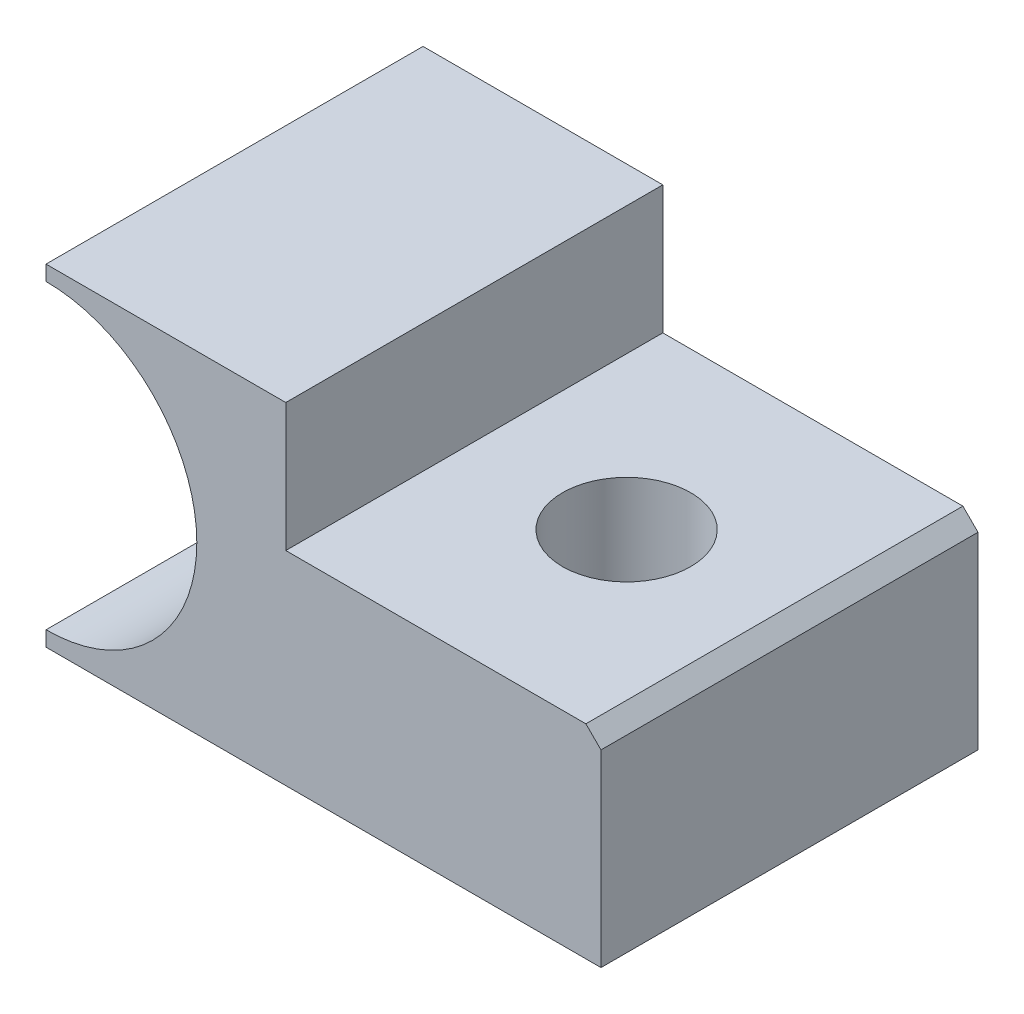
SolidWorks part; units mm, degrees
material "AISI Type A2 Tool Steel Custom"
ref_plane "Front Plane" through (0, 0, 0) normal (0, 0, 1) x (1, 0, 0)
ref_plane "Top Plane" through (0, 0, 0) normal (0, 1, 0) x (1, 0, 0)
ref_plane "Right Plane" through (0, 0, 0) normal (1, 0, 0) x (0, 0, -1)
sketch "Sketch1" plane through (0, 0, 0) normal (0, 0, 1) x (1, 0, 0)
  line L4 (46.736, 0) -> (46.736, 17.145)
  line L6 (20.193, 27.94) -> (20.193, 17.145)
  line L7 (20.193, 17.145) -> (46.736, 17.145)
  line L9 (0, 26.67) -> (0, 27.94)
  line L10 (0, 27.94) -> (20.193, 27.94)
  line L11 (0, 1.27) -> (0, 0)
  line L12 (0, 0) -> (46.736, 0)
  arc A1 (0, 1.27) -> (0, 26.67) centre (0, 13.97) ccw
  dimension "D2" = 25.4
  dimension "D1" = 10.795
  dimension "D3" = 17.145
  dimension "D4" = 46.736
  dimension "D5" = 26.543
  dimension "D6" = 1.27
  dimension "D7" = 1.27
extrude "Boss-Extrude1" add sketch "Sketch1" along normal blind 31.75
sketch "Sketch5" plane through (0, 17.145, 0) normal (0, 1, 0) x (1, 0, 0)
  line L2 (0, -31.75) -> (0, 0) construction
  point P0 (33.02, -15.875)
  point P12 (0, -15.875)
  dimension "D1" = 33.02
hole_wizard "X (0.397) Diameter Hole1" positions "Sketch5" profile "Sketch4" hole size "X" standard "ANSI Inch" end condition through all
sketch "Sketch4" plane through (33.02, 17.145, 15.875) normal (1, 0, 0) x (0, 0, 1)
  line L0 (0, 0) -> (0, 17.145)
  line L1 (0, 17.145) -> (5.3975, 17.145)
  line L2 (5.3975, 17.145) -> (5.3975, 0)
  line L5 (5.3975, 0) -> (0, 0)
  line L11 (0, -6.35) -> (0, 107.95) construction
  dimension "Thru Hole Dia." = 10.795
  dimension "Thru Hole Depth" = 17.145
chamfer "Chamfer1" distance 1.27 angle 45 1 edges at (46.736, 17.145, 15.875)
